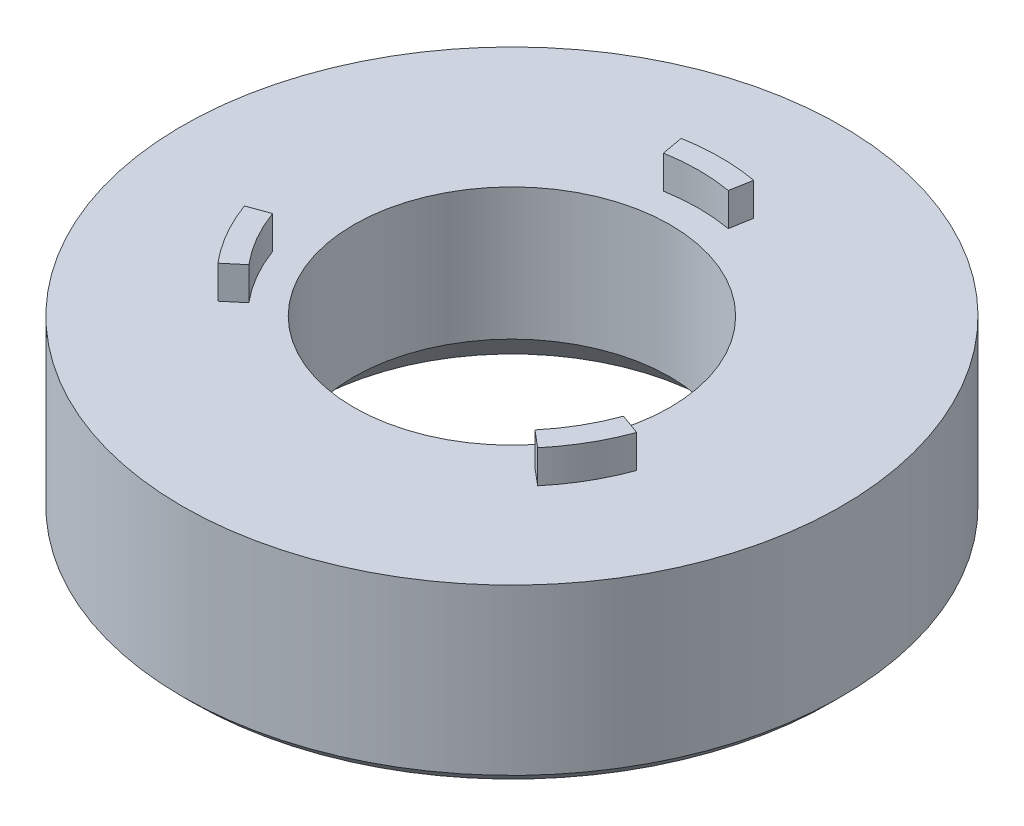
SolidWorks part; units mm, degrees
ref_plane "前视基准面" through (0, 0, 0) normal (0, 0, 1) x (1, 0, 0)
ref_plane "上视基准面" through (0, 0, 0) normal (0, 1, 0) x (1, 0, 0)
ref_plane "右视基准面" through (0, 0, 0) normal (1, 0, 0) x (0, 0, -1)
sketch "草图1" plane through (0, 0, 0) normal (0, 1, 0) x (1, 0, 0)
  circle A0 centre (0, 0) radius 7.2
  circle A1 centre (0, 0) radius 15
  dimension "D1" = 14.4
  dimension "D2" = 30
extrude "凸台-拉伸1" add sketch "草图1" along normal blind 8
chamfer "倒角1" distance 0.5 angle 45 1 edges at (0, 0, 15)
chamfer "倒角2" distance 2 angle 45 1 edges at (0, 0, 7.2)
sketch "草图2" plane through (0, 8, 0) normal (0, 1, 0) x (1, 0, 0)
  line L0 (0, 0) -> (0, 9.5) construction
  line L2 (1.6497, 9.3557) -> (1.476, 8.3709)
  line L3 (-1.6497, 9.3557) -> (-1.476, 8.3709)
  line L4 (1.476, 8.3709) -> (0, 0) construction
  line L5 (-1.476, 8.3709) -> (0, 0) construction
  arc A0 (1.6497, 9.3557) -> (-1.6497, 9.3557) centre (0, 0) ccw
  arc A1 (1.476, 8.3709) -> (-1.476, 8.3709) centre (0, 0) ccw
  arc A2 (-1.6497, 9.3557) -> (1.6497, 9.3557) centre (0, 0) ccw construction
  arc A3 (-1.476, 8.3709) -> (1.476, 8.3709) centre (0, 0) ccw construction
  point P6 (0, 0)
  point P8 (0, 0)
  dimension "D1" = 17
  dimension "D2" = 19
  dimension "D3" = 10
extrude "凸台-拉伸2" add sketch "草图2" along normal blind 1.5
pattern_circular "阵列(圆周)1" count 3 over 360 about axis through (0, 0, 0) along (0, 1, 0) of "凸台-拉伸2"
